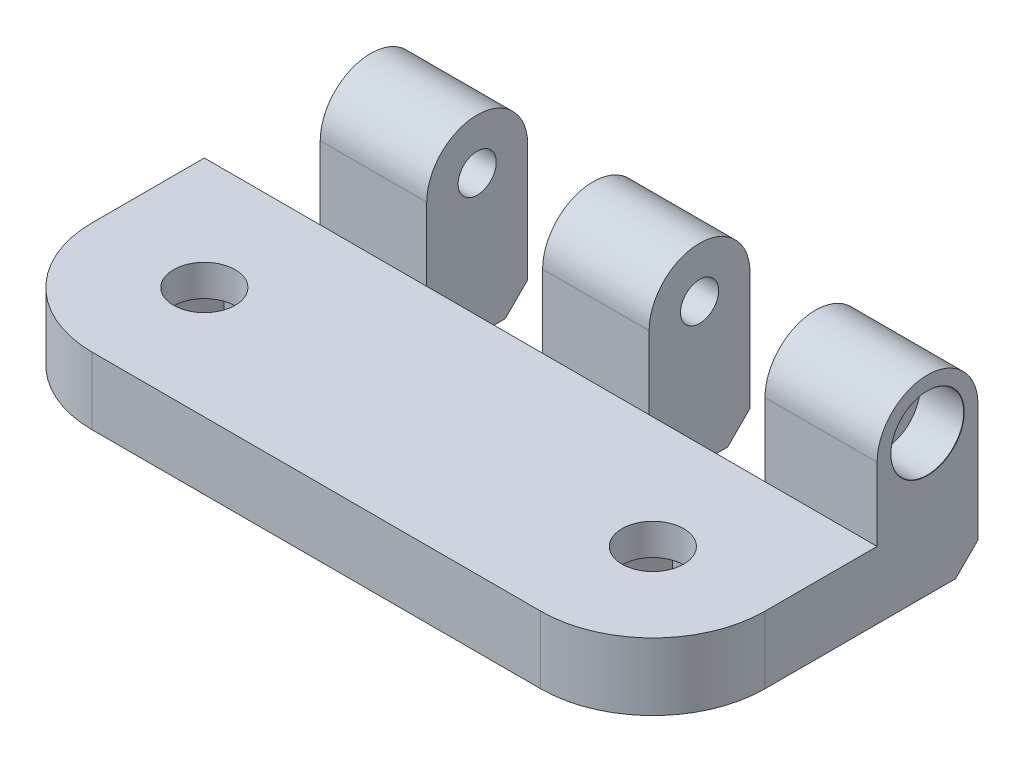
SolidWorks part; units mm, degrees
ref_plane "Front Plane" through (0, 0, 0) normal (0, 0, 1) x (1, 0, 0)
ref_plane "Top Plane" through (0, 0, 0) normal (0, 1, 0) x (1, 0, 0)
ref_plane "Right Plane" through (0, 0, 0) normal (1, 0, 0) x (0, 0, -1)
sketch "Sketch1" plane through (0, 0, 0) normal (1, 0, 0) x (0, 0, -1)
  line L0 (4.5, 0) -> (4.5, -12.5)
  line L1 (4.5, -12.5) -> (-24.5, -12.5)
  line L2 (-24.5, -12.5) -> (-24.5, -6.5)
  line L3 (-24.5, -6.5) -> (-4.5, -6.5)
  line L4 (-4.5, 0) -> (-4.5, -6.5)
  arc A0 (4.5, 0) -> (-4.5, 0) centre (0, 0) ccw
  dimension "D1" = 9
  dimension "D2" = 6.5
  dimension "D3" = 6
  dimension "D4" = 20
extrude "Boss-Extrude1" add sketch "Sketch1" against normal mid plane 60
chamfer "Chamfer1" distance 2 angle 45 1 edges at (0, -12.5, -4.5)
fillet "Fillet1" radius 10 2 edges at (-30, -9.5, 24.5) (30, -9.5, 24.5)
sketch "Sketch2" plane through (0, -12.5, 0) normal (0, -1, 0) x (1, 0, 0)
  line L0 (30, -4.5) -> (-30, -4.5) construction
  line L1 (-30, 4.5) -> (-19.6667, 4.5)
  line L2 (-30, 4.5) -> (-30, -4.5)
  line L3 (-30, -4.5) -> (-19.6667, -4.5)
  line L4 (-19.6667, 4.5) -> (-19.6667, -4.5)
  line L6 (-10.1667, 4.5) -> (0.1667, 4.5)
  line L7 (-10.1667, 4.5) -> (-10.1667, -4.5)
  line L8 (-10.1667, -4.5) -> (0.1667, -4.5)
  line L9 (0.1667, 4.5) -> (0.1667, -4.5)
  line L10 (9.6667, 4.5) -> (20, 4.5)
  line L11 (9.6667, 4.5) -> (9.6667, -4.5)
  line L12 (9.6667, -4.5) -> (20, -4.5)
  line L13 (20, 4.5) -> (20, -4.5)
  line L15 (20, 4.5) -> (30, 4.5) construction
  line L16 (30, 14.5) -> (30, -2.5) construction
  line L17 (-30, 4.5) -> (30, 4.5) construction
  dimension "D1" = 10
  dimension "D2" = 9.5
  dimension "D3" = 9.5
extrude "Cut-Extrude1" cut sketch "Sketch2" against normal through all
hole_wizard "CBORE for M3 Hex Socket Head Cap Screw1" positions "Sketch3" profile "Sketch5" counterbore size "M3" standard "DIN" end condition through all
sketch "Sketch3" plane through (30, 0, 0) normal (1, 0, 0) x (0, 0, -1)
  point P0 (0, 0)
sketch "Sketch5" plane through (30, 0, 0) normal (0, 1, 0) x (0, 0, -1)
  line L0 (0, 0) -> (0, 60)
  line L1 (0, 60) -> (1.7, 60)
  line L3 (1.7, 60) -> (1.7, 3.9)
  line L4 (3.25, 3.9) -> (1.7, 3.9)
  line L5 (3.25, 3.9) -> (3.25, 0.025)
  line L6 (3.25, 0.025) -> (3.275, 0)
  line L7 (3.275, 0) -> (0, 0)
  line L8 (-3.25, 0.025) -> (-3.275, 0) construction
  line L11 (0, -6.35) -> (0, 107.95) construction
  dimension "Thru Hole Dia." = 3.4
  dimension "Thru Hole Depth" = 60
  dimension "C'Bore Dia." = 6.5
  dimension "C'Bore Depth" = 3.9
  dimension "Near C'Sink Dia." = 6.55
  dimension "Near C'Sink Angle" = 90
sketch "Sketch6" plane through (0, -12.5, 0) normal (0, -1, 0) x (1, 0, 0)
  line L0 (17.604, 18.65) -> (-17.604, 18.65) construction
  line L1 (24.792, 14.5) -> (22.396, 18.65)
  line L2 (22.396, 18.65) -> (17.604, 18.65)
  line L3 (17.604, 18.65) -> (15.208, 14.5)
  line L4 (15.208, 14.5) -> (17.604, 10.35)
  line L5 (17.604, 10.35) -> (22.396, 10.35)
  line L6 (22.396, 10.35) -> (24.792, 14.5)
  line L7 (-15.208, 14.5) -> (-17.604, 18.65)
  line L8 (-17.604, 18.65) -> (-22.396, 18.65)
  line L9 (-22.396, 18.65) -> (-24.792, 14.5)
  line L10 (-24.792, 14.5) -> (-22.396, 10.35)
  line L11 (-22.396, 10.35) -> (-17.604, 10.35)
  line L12 (-17.604, 10.35) -> (-15.208, 14.5)
  line L13 (-17.604, 10.35) -> (17.604, 10.35) construction
  circle A0 centre (20, 14.5) radius 4.15 construction
  circle A1 centre (-20, 14.5) radius 4.15 construction
  arc A2 (-20, 24.5) -> (-30, 14.5) centre (-20, 14.5) ccw construction
  dimension "D1" = 8.3
extrude "Cut-Extrude2" cut sketch "Sketch6" against normal blind 3.2
sketch "Sketch7" plane through (0, -9.3, 0) normal (0, -1, 0) x (1, 0, 0)
  line L0 (-20, 18.65) -> (-20, 14.5) construction
  line L1 (-17.604, 18.65) -> (-22.396, 18.65) construction
  line L2 (-20, 14.5) -> (-15.208, 14.5) construction
  line L3 (24.792, 14.5) -> (20, 14.5) construction
  line L4 (20, 14.5) -> (20, 18.65) construction
  line L5 (22.396, 18.65) -> (17.604, 18.65) construction
  circle A0 centre (-20, 14.5) radius 2.75
  circle A1 centre (20, 14.5) radius 2.75
  dimension "D1" = 5.5
extrude "Cut-Extrude3" cut sketch "Sketch7" against normal up to surface (2.8 mm away) up to face at (0, -6.5, 10.3311)
